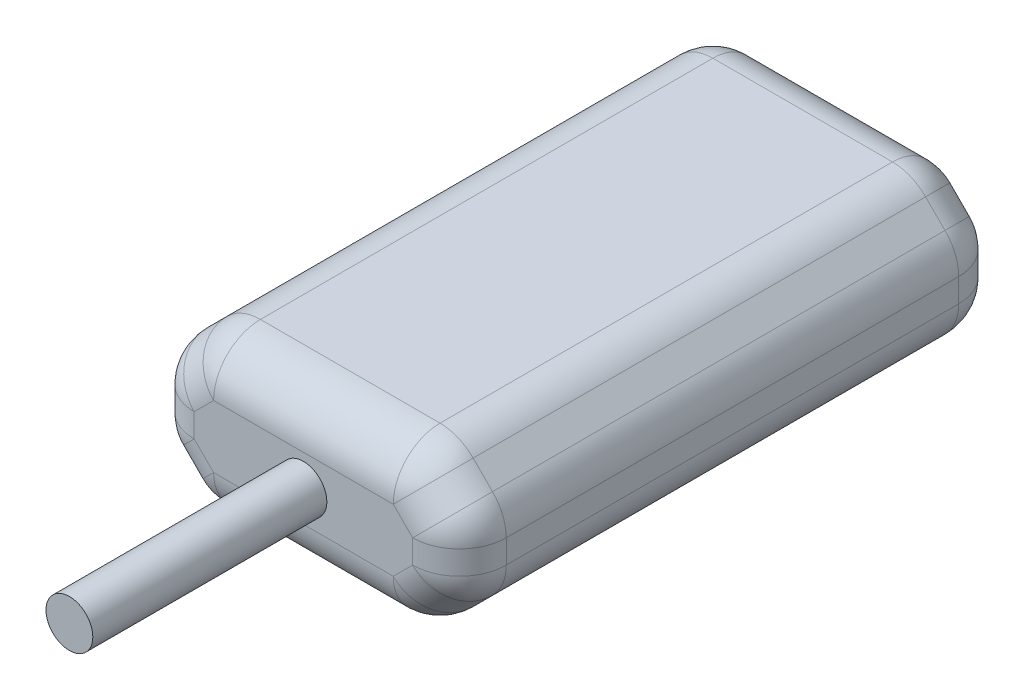
SolidWorks part; units mm, degrees
ref_plane "前视基准面" through (0, 0, 0) normal (0, 0, 1) x (1, 0, 0)
ref_plane "上视基准面" through (0, 0, 0) normal (0, 1, 0) x (1, 0, 0)
ref_plane "右视基准面" through (0, 0, 0) normal (1, 0, 0) x (0, 0, -1)
other "Configuration Table"
sketch "草图1" plane through (0, 0, 0) normal (0, 0, 1) x (1, 0, 0)
  line L0 (0, 0) -> (0, 10)
  line L1 (0, 10) -> (20, 10)
  line L2 (20, 10) -> (20, 0)
  line L3 (20, 0) -> (0, 0)
extrude "凸台-拉伸1" add sketch "草图1" along normal blind 35
chamfer "倒角2" distance 3 angle 45 4 edges at (20, 0, 17.5) (0, 0, 17.5) (0, 10, 17.5) (20, 10, 17.5)
fillet "圆角1" radius 3 24 edges at (18.5, 8.5, 0) (10, 10, 0) (1.5, 8.5, 0) (0, 5, 0) (1.5, 1.5, 0) (10, 0, 0) (18.5, 1.5, 0) (20, 5, 0) (1.5, 1.5, 35) (0, 5, 35) (1.5, 8.5, 35) (10, 10, 35) (18.5, 8.5, 35) (20, 5, 35) (18.5, 1.5, 35) (10, 0, 35) (3, 0, 17.5) (0, 3, 17.5) (0, 7, 17.5) (3, 10, 17.5) (17, 0, 17.5) (20, 3, 17.5) (20, 7, 17.5) (17, 10, 17.5)
sketch "草图2" plane through (0, 0, 35) normal (0, 0, 1) x (1, 0, 0)
  line L0 (3, 5) -> (17, 5) construction
  line L1 (3, 5.7574) -> (3, 4.2426) construction
  line L2 (17, 4.2426) -> (17, 5.7574) construction
  circle A0 centre (10, 5) radius 1.5
extrude "凸台-拉伸2" add sketch "草图2" along normal blind 15
